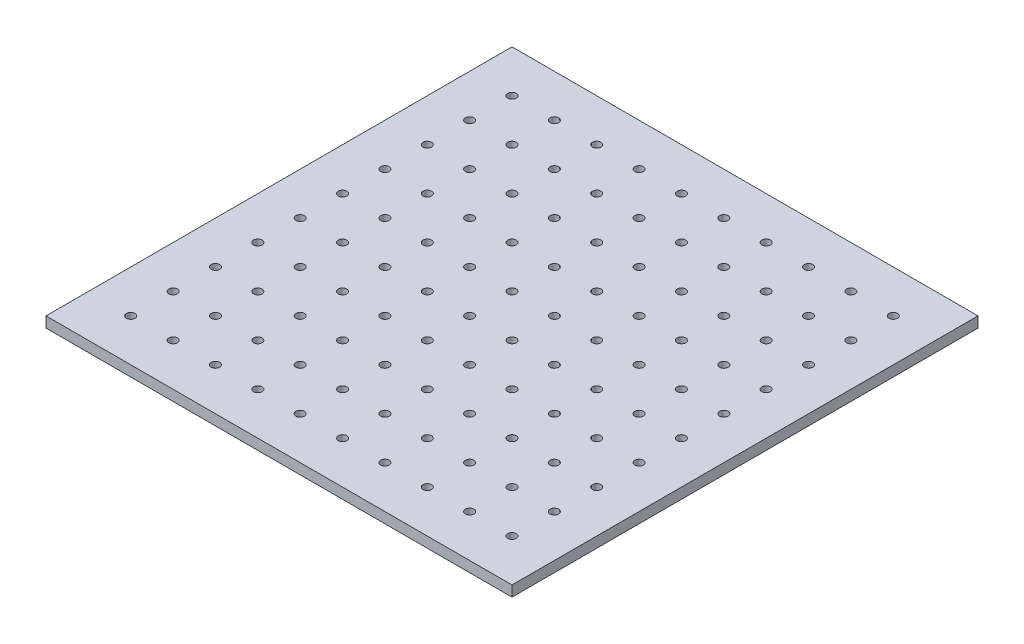
SolidWorks part; units mm, degrees
ref_plane "Front Plane" through (0, 0, 0) normal (0, 0, 1) x (1, 0, 0)
ref_plane "Top Plane" through (0, 0, 0) normal (0, 1, 0) x (1, 0, 0)
ref_plane "Right Plane" through (0, 0, 0) normal (1, 0, 0) x (0, 0, -1)
sketch "Sketch1" plane through (0, 0, 0) normal (0, 1, 0) x (1, 0, 0)
  line L1 (-25.4, 254) -> (254, 254)
  line L2 (-25.4, 254) -> (-25.4, -25.4)
  line L3 (-25.4, -25.4) -> (254, -25.4)
  line L4 (254, 254) -> (254, -25.4)
  circle A0 centre (0, 0) radius 2.5527
  circle A1 centre (25.4, 0) radius 2.5527
  circle A2 centre (50.8, 0) radius 2.5527
  circle A3 centre (76.2, 0) radius 2.5527
  circle A4 centre (101.6, 0) radius 2.5527
  circle A5 centre (127, 0) radius 2.5527
  circle A6 centre (152.4, 0) radius 2.5527
  circle A7 centre (177.8, 0) radius 2.5527
  circle A8 centre (203.2, 0) radius 2.5527
  circle A9 centre (228.6, 0) radius 2.5527
  circle A10 centre (0, 25.4) radius 2.5527
  circle A11 centre (25.4, 25.4) radius 2.5527
  circle A12 centre (50.8, 25.4) radius 2.5527
  circle A13 centre (76.2, 25.4) radius 2.5527
  circle A14 centre (101.6, 25.4) radius 2.5527
  circle A15 centre (127, 25.4) radius 2.5527
  circle A16 centre (152.4, 25.4) radius 2.5527
  circle A17 centre (177.8, 25.4) radius 2.5527
  circle A18 centre (203.2, 25.4) radius 2.5527
  circle A19 centre (228.6, 25.4) radius 2.5527
  circle A20 centre (0, 50.8) radius 2.5527
  circle A21 centre (25.4, 50.8) radius 2.5527
  circle A22 centre (50.8, 50.8) radius 2.5527
  circle A23 centre (76.2, 50.8) radius 2.5527
  circle A24 centre (101.6, 50.8) radius 2.5527
  circle A25 centre (127, 50.8) radius 2.5527
  circle A26 centre (152.4, 50.8) radius 2.5527
  circle A27 centre (177.8, 50.8) radius 2.5527
  circle A28 centre (203.2, 50.8) radius 2.5527
  circle A29 centre (228.6, 50.8) radius 2.5527
  circle A30 centre (0, 76.2) radius 2.5527
  circle A31 centre (25.4, 76.2) radius 2.5527
  circle A32 centre (50.8, 76.2) radius 2.5527
  circle A33 centre (76.2, 76.2) radius 2.5527
  circle A34 centre (101.6, 76.2) radius 2.5527
  circle A35 centre (127, 76.2) radius 2.5527
  circle A36 centre (152.4, 76.2) radius 2.5527
  circle A37 centre (177.8, 76.2) radius 2.5527
  circle A38 centre (203.2, 76.2) radius 2.5527
  circle A39 centre (228.6, 76.2) radius 2.5527
  circle A40 centre (0, 101.6) radius 2.5527
  circle A41 centre (25.4, 101.6) radius 2.5527
  circle A42 centre (50.8, 101.6) radius 2.5527
  circle A43 centre (76.2, 101.6) radius 2.5527
  circle A44 centre (101.6, 101.6) radius 2.5527
  circle A45 centre (127, 101.6) radius 2.5527
  circle A46 centre (152.4, 101.6) radius 2.5527
  circle A47 centre (177.8, 101.6) radius 2.5527
  circle A48 centre (203.2, 101.6) radius 2.5527
  circle A49 centre (228.6, 101.6) radius 2.5527
  circle A50 centre (0, 127) radius 2.5527
  circle A51 centre (25.4, 127) radius 2.5527
  circle A52 centre (50.8, 127) radius 2.5527
  circle A53 centre (76.2, 127) radius 2.5527
  circle A54 centre (101.6, 127) radius 2.5527
  circle A55 centre (127, 127) radius 2.5527
  circle A56 centre (152.4, 127) radius 2.5527
  circle A57 centre (177.8, 127) radius 2.5527
  circle A58 centre (203.2, 127) radius 2.5527
  circle A59 centre (228.6, 127) radius 2.5527
  circle A60 centre (0, 152.4) radius 2.5527
  circle A61 centre (25.4, 152.4) radius 2.5527
  circle A62 centre (50.8, 152.4) radius 2.5527
  circle A63 centre (76.2, 152.4) radius 2.5527
  circle A64 centre (101.6, 152.4) radius 2.5527
  circle A65 centre (127, 152.4) radius 2.5527
  circle A66 centre (152.4, 152.4) radius 2.5527
  circle A67 centre (177.8, 152.4) radius 2.5527
  circle A68 centre (203.2, 152.4) radius 2.5527
  circle A69 centre (228.6, 152.4) radius 2.5527
  circle A70 centre (0, 177.8) radius 2.5527
  circle A71 centre (25.4, 177.8) radius 2.5527
  circle A72 centre (50.8, 177.8) radius 2.5527
  circle A73 centre (76.2, 177.8) radius 2.5527
  circle A74 centre (101.6, 177.8) radius 2.5527
  circle A75 centre (127, 177.8) radius 2.5527
  circle A76 centre (152.4, 177.8) radius 2.5527
  circle A77 centre (177.8, 177.8) radius 2.5527
  circle A78 centre (203.2, 177.8) radius 2.5527
  circle A79 centre (228.6, 177.8) radius 2.5527
  circle A80 centre (0, 203.2) radius 2.5527
  circle A81 centre (25.4, 203.2) radius 2.5527
  circle A82 centre (50.8, 203.2) radius 2.5527
  circle A83 centre (76.2, 203.2) radius 2.5527
  circle A84 centre (101.6, 203.2) radius 2.5527
  circle A85 centre (127, 203.2) radius 2.5527
  circle A86 centre (152.4, 203.2) radius 2.5527
  circle A87 centre (177.8, 203.2) radius 2.5527
  circle A88 centre (203.2, 203.2) radius 2.5527
  circle A89 centre (228.6, 203.2) radius 2.5527
  circle A90 centre (0, 228.6) radius 2.5527
  circle A91 centre (25.4, 228.6) radius 2.5527
  circle A92 centre (50.8, 228.6) radius 2.5527
  circle A93 centre (76.2, 228.6) radius 2.5527
  circle A94 centre (101.6, 228.6) radius 2.5527
  circle A95 centre (127, 228.6) radius 2.5527
  circle A96 centre (152.4, 228.6) radius 2.5527
  circle A97 centre (177.8, 228.6) radius 2.5527
  circle A98 centre (203.2, 228.6) radius 2.5527
  circle A99 centre (228.6, 228.6) radius 2.5527
  dimension "D1" = 10
  dimension "D2" = 10
extrude "Boss-Extrude1" add sketch "Sketch1" along normal blind 6.35
